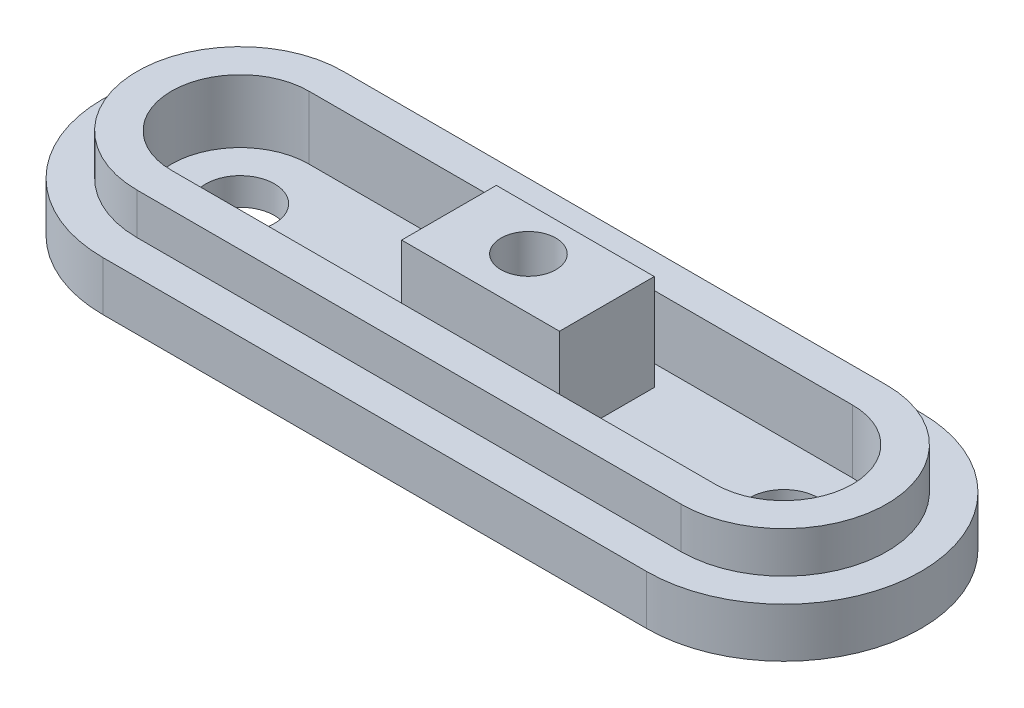
SolidWorks part; units mm, degrees
ref_plane "Alzado" through (0, 0, 0) normal (0, 0, 1) x (1, 0, 0)
ref_plane "Planta" through (0, 0, 0) normal (0, 1, 0) x (1, 0, 0)
ref_plane "Vista lateral" through (0, 0, 0) normal (1, 0, 0) x (0, 0, -1)
sketch "Croquis1" plane through (0, 0, 0) normal (0, 1, 0) x (1, 0, 0)
  line L0 (0, 125.0037) -> (0, -125.6582) construction
  line L1 (-206.8124, -0.3272) -> (223.8286, -0.3272) construction
  line L2 (-167.5443, 125.0037) -> (-167.5443, -125.6582) construction
  line L3 (178.0158, 125.0037) -> (178.0158, -125.6582) construction
  line L5 (-194.3238, -100.3272) -> (201.6762, -100.3272)
  line L6 (-194.3238, 99.6728) -> (201.6762, 99.6728)
  arc A0 (-194.3238, -100.3272) -> (-194.3238, 99.6728) centre (-194.3238, -0.3272) cw
  arc A1 (201.6762, -100.3272) -> (201.6762, 99.6728) centre (201.6762, -0.3272) ccw
  dimension "D1" = 396
extrude "Saliente-Extruir1" add sketch "Croquis1" along normal mid plane 36
sketch "Croquis2" plane through (0, 18, 0) normal (0, 1, 0) x (1, 0, 0)
  line L3 (-194.3238, -75.3272) -> (201.6762, -75.3272)
  line L4 (-194.3238, 74.6728) -> (201.6762, 74.6728)
  arc A0 (-194.3238, -75.3272) -> (-194.3238, 74.6728) centre (-194.3238, -0.3272) cw
  arc A1 (201.6762, -75.3272) -> (201.6762, 74.6728) centre (201.6762, -0.3272) ccw
sketch "Croquis3" plane through (0, 0, 0) normal (0, 1, 0) x (1, 0, 0)
  line L1 (-194.3238, -50.3272) -> (201.6762, -50.3272)
  line L2 (-194.3238, 49.6728) -> (201.6762, 49.6728)
  arc A0 (-194.3238, -50.3272) -> (-194.3238, 49.6728) centre (-194.3238, -0.3272) cw
  arc A1 (201.6762, -50.3272) -> (201.6762, 49.6728) centre (201.6762, -0.3272) ccw
extrude "Saliente-Extruir6" add sketch "Croquis2" along normal blind 66 from surface at -36 starting at face at (3.6762, -18, 0.3272)
extrude "Cortar-Extruir1" cut sketch "Croquis3" against normal blind 46 from surface at 48 starting at face at (3.6762, 48, 0.3272)
sketch "Croquis4" plane through (0, 0, 0) normal (0, 1, 0) x (1, 0, 0)
  line L0 (-194.3238, 107.2181) -> (-194.3238, -127.2441) construction
  line L1 (202.0673, 107.2181) -> (202.0673, -127.2441) construction
  circle A0 centre (-194.3238, -0.3272) radius 25
  circle A1 centre (201.6762, -0.3272) radius 25
extrude "Cortar-Extruir2" cut sketch "Croquis4" against normal through all from surface at 18 starting at face at (3.6762, 18, 0.3272)
sketch "Croquis5" plane through (0, 0, 0) normal (0, 0, 1) x (1, 0, 0)
  line L0 (14.9616, -79.8537) -> (14.9616, 125.8853) construction
  line L1 (-42.5384, 72) -> (72.4616, 72)
  line L3 (-42.5384, -18) -> (72.4616, -18)
  line L4 (-42.5384, -18) -> (-42.5384, 72)
  line L5 (72.4616, -18) -> (72.4616, 72)
  point P6 (0, 0)
  dimension "D1" = 90
extrude "Saliente-Extruir7" add sketch "Croquis5" along normal mid plane 69
sketch "Croquis7" plane through (0, 0, 0) normal (0, 1, 0) x (1, 0, 0)
  circle A0 centre (12.3671, 2.964) radius 20
extrude "Cortar-Extruir3" cut sketch "Croquis7" against normal through all from surface at 72 starting at face at (14.9616, 72, 0)
